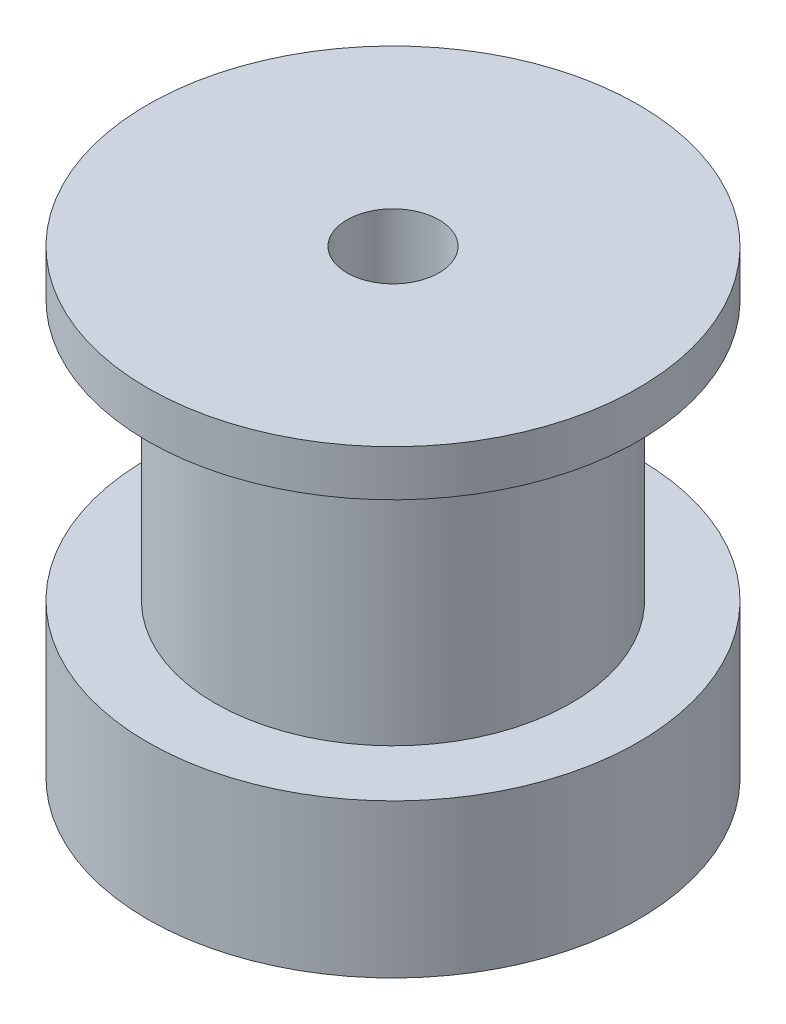
SolidWorks part; units mm, degrees
ref_plane "Front Plane" through (0, 0, 0) normal (0, 0, 1) x (1, 0, 0)
ref_plane "Top Plane" through (0, 0, 0) normal (0, 1, 0) x (1, 0, 0)
ref_plane "Right Plane" through (0, 0, 0) normal (1, 0, 0) x (0, 0, -1)
sketch "Sketch1" plane through (0, 0, 0) normal (0, 1, 0) x (1, 0, 0)
  circle A0 centre (0, 0) radius 8
  dimension "D1" = 16
extrude "Boss-Extrude1" add sketch "Sketch1" along normal blind 5
sketch "Sketch2" plane through (0, 5, 0) normal (0, 1, 0) x (1, 0, 0)
  circle A0 centre (0, 0) radius 5.8
  dimension "D1" = 11.6
extrude "Boss-Extrude2" add sketch "Sketch2" along normal blind 8.5
sketch "Sketch3" plane through (0, 13.5, 0) normal (0, 1, 0) x (1, 0, 0)
  circle A0 centre (0, 0) radius 8
  dimension "D1" = 16
extrude "Boss-Extrude3" add sketch "Sketch3" along normal blind 1.5
sketch "Sketch4" plane through (0, 15, 0) normal (0, 1, 0) x (1, 0, 0)
  circle A0 centre (0, 0) radius 1.5
  dimension "D1" = 3
extrude "Cut-Extrude1" cut sketch "Sketch4" against normal blind 15
